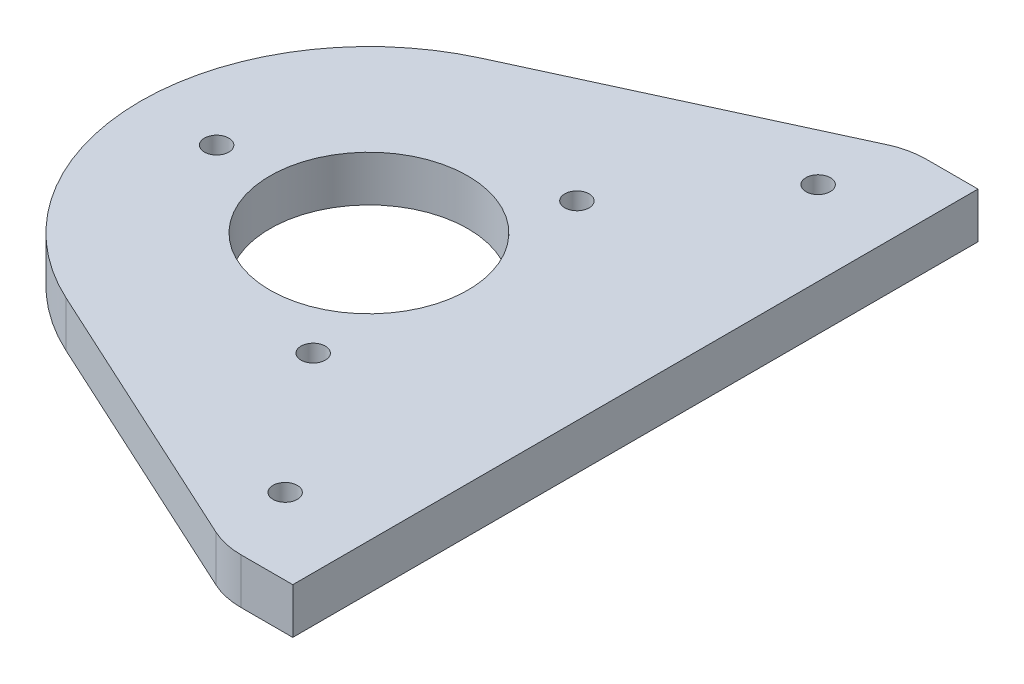
SolidWorks part; units mm, degrees
material "Thornel Mat VMA"
ref_plane "前视基准面" through (0, 0, 0) normal (0, 0, 1) x (1, 0, 0)
ref_plane "上视基准面" through (0, 0, 0) normal (0, 1, 0) x (1, 0, 0)
ref_plane "右视基准面" through (0, 0, 0) normal (1, 0, 0) x (0, 0, -1)
other "Configuration Table"
sketch "草图1" plane through (0, 0, 0) normal (0, 1, 0) x (1, 0, 0)
  line L0 (23.7739, 45) -> (23.7739, -45)
  line L1 (-23.7739, -27.2498) -> (23.7739, -27.2498) construction
  line L3 (-23.7739, 27.2498) -> (23.7739, 27.2498) construction
  line L4 (23.7739, -27.2498) -> (23.7739, 27.2498) construction
  line L5 (-23.7739, -27.2498) -> (23.7739, 27.2498) construction
  line L6 (-23.7739, 27.2498) -> (23.7739, -27.2498) construction
  line L9 (-97.7262, 0) -> (103.7649, 0) construction
  line L10 (23.7739, 45) -> (14.7739, 45)
  line L11 (14.7739, 45) -> (-23.7739, 27.2498)
  line L12 (-23.7739, -27.2498) -> (14.7739, -45)
  line L13 (14.7739, -45) -> (23.7739, -45)
  arc A0 (-23.7739, 27.2498) -> (-23.7739, -27.2498) centre (-11.2261, 0) ccw
  point P0 (0, 0)
  dimension "D1" = 30
  dimension "D2" = 35
  dimension "D3" = 90
  dimension "D4" = 9
  dimension "D5" = 9
extrude "凸台-拉伸1" add sketch "草图1" along normal blind 6
sketch "草图2" plane through (0, 6, 0) normal (0, 1, 0) x (1, 0, 0)
  circle A0 centre (-11.2261, 0) radius 13
  circle A1 centre (-31.2261, 0) radius 1.6
  circle A2 centre (-1.2261, -17.3205) radius 1.6
  circle A3 centre (-1.2261, 17.3205) radius 1.6
  point P5 (0, 0)
  point P6 (-38.718, 16.5142)
  point P7 (0, 0)
  point P12 (-11.2261, 0)
  dimension "D1" = 26
  dimension "D3" = 3.2
  dimension "D4" = 20
  dimension "D2" = 3
extrude "切除-拉伸1" cut sketch "草图2" against normal up to surface (6 mm away) up to face at (2.0159, 0, 0)
fillet "圆角1" radius 10 2 edges at (14.7739, 3, 45) (14.7739, 3, -45)
sketch "草图3" plane through (0, 6, 0) normal (0, 1, 0) x (1, 0, 0)
  line L0 (-54.4006, 0) -> (69.8461, 0) construction
  line L1 (23.7739, -45) -> (23.7739, 45) construction
  line L2 (23.7739, 45) -> (16.9656, 45) construction
  circle A0 centre (12.7739, 35) radius 1.6
  circle A1 centre (12.7739, -35) radius 1.6
  dimension "D1" = 3.2
  dimension "D2" = 11
  dimension "D3" = 10
extrude "切除-拉伸2" cut sketch "草图3" against normal up to surface (6 mm away) up to face at (-1.2261, 0, -15.7205)
